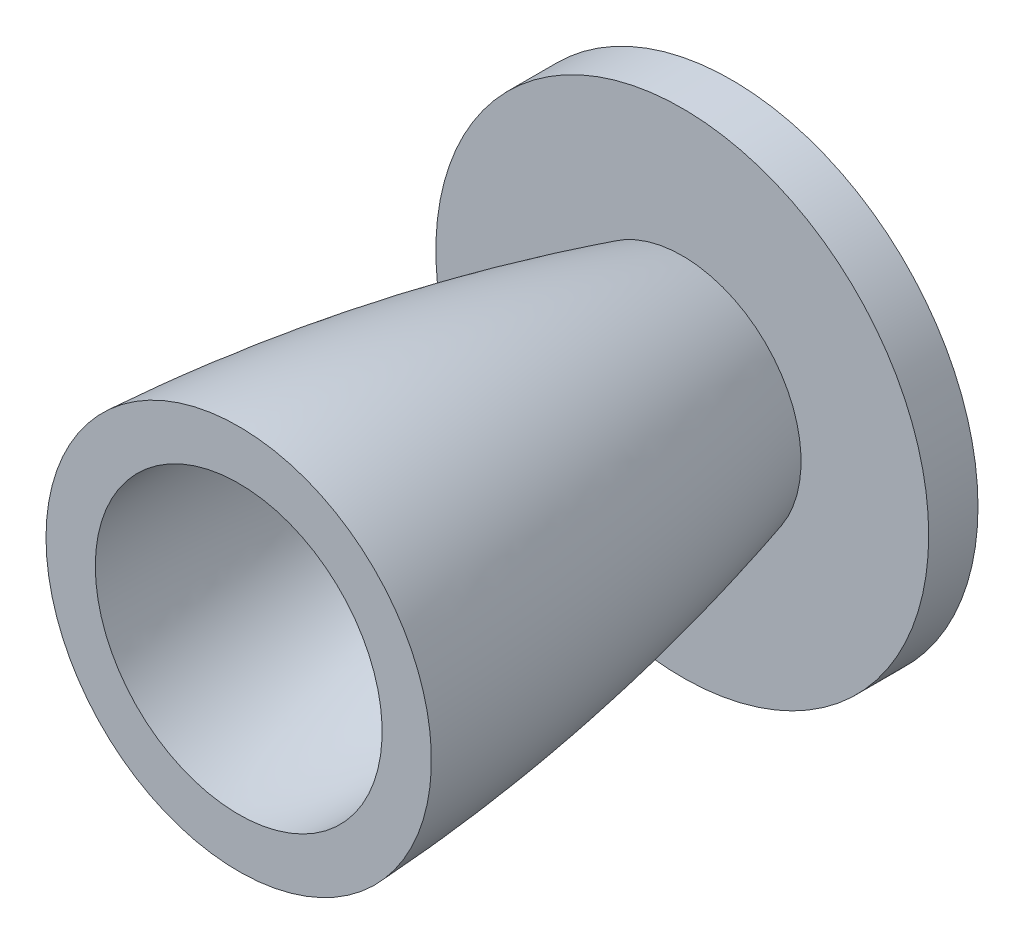
SolidWorks part; units mm, degrees
ref_plane "Front Plane" through (0, 0, 0) normal (0, 0, 1) x (1, 0, 0)
ref_plane "Top Plane" through (0, 0, 0) normal (0, 1, 0) x (1, 0, 0)
ref_plane "Right Plane" through (0, 0, 0) normal (1, 0, 0) x (0, 0, -1)
sketch "Sketch1" plane through (0, 0, 0) normal (0, 0, 1) x (1, 0, 0)
  circle A0 centre (0, 0) radius 500
extrude "Boss-Extrude1" add sketch "Sketch1" along normal blind 100
sketch "Sketch2" plane through (0, 0, 0) normal (0, 1, 0) x (1, 0, 0)
  line L0 (0, 166.8498) -> (0, -541.683) construction
  line L1 (191.0011, -281.6172) -> (91.0011, -281.6172)
  line L2 (91.0011, -281.6172) -> (91.0011, -100)
  line L3 (91.0011, -100) -> (241.0011, -100)
  line L4 (-500, -100) -> (500, -100) construction
  line L6 (291.0011, -1000) -> (391.0011, -1000)
  spline S0 degree 2 poles (241.0011, -100) (365.6451, -541.845) (391.0011, -1000) knots 0 0 0 1 1 1
  spline S1 degree 2 poles (191.0011, -281.6172) (305.655, -631.7983) (291.0011, -1000) knots 0 0 0 1 1 1
  dimension "D1" = 181.6172
  dimension "D2" = 150
  dimension "D3" = 200
  dimension "D4" = 100
  dimension "D5" = 100
revolve "Revolve2" add sketch "Sketch2" angle 360 about L0
